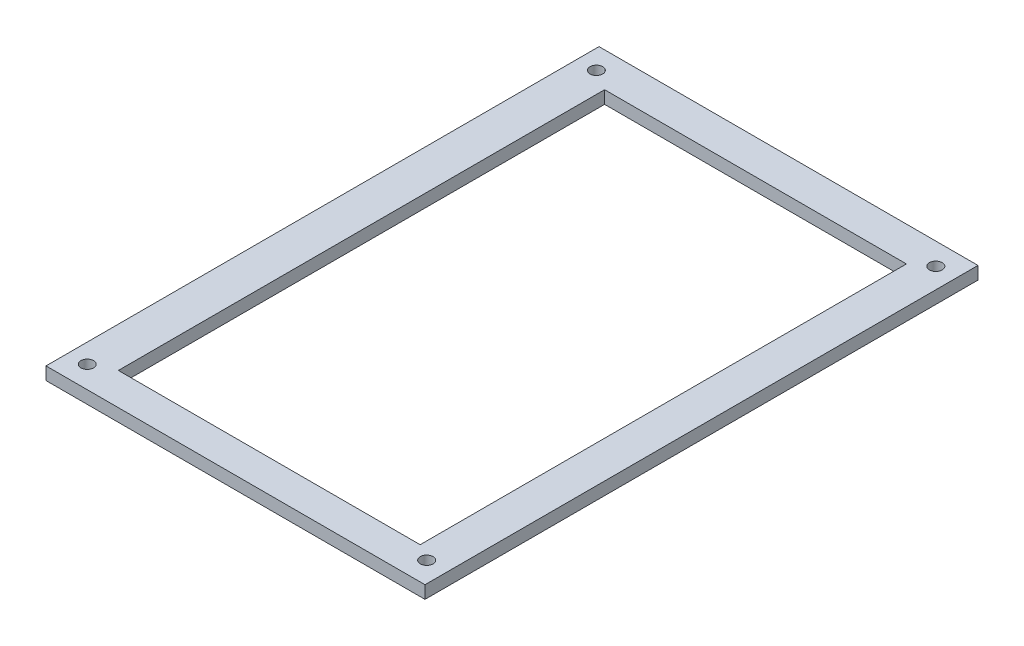
SolidWorks part; units mm, degrees
ref_plane "Front Plane" through (0, 0, 0) normal (0, 0, 1) x (1, 0, 0)
ref_plane "Top Plane" through (0, 0, 0) normal (0, 1, 0) x (1, 0, 0)
ref_plane "Right Plane" through (0, 0, 0) normal (1, 0, 0) x (0, 0, -1)
sketch "Sketch1" plane through (0, 0, 0) normal (0, 1, 0) x (1, 0, 0)
  line L1 (0, 0) -> (97, 0)
  line L2 (0, 0) -> (0, 200)
  line L3 (0, 200) -> (97, 200)
  line L4 (97, 0) -> (97, 200)
  dimension "D1" = 97
  dimension "D2" = 200
extrude "Boss-Extrude1" add sketch "Sketch1" along normal blind 42
sketch "Sketch3" plane through (0, 42, 0) normal (0, 1, 0) x (1, 0, 0)
  line L0 (0, 0) -> (97, 0) construction
  line L1 (97, 0) -> (97, 200) construction
  circle A0 centre (88.5, 61) radius 1.5
  circle A1 centre (8.5, 61) radius 1.5
  circle A2 centre (88.5, 181) radius 1.5
  circle A3 centre (8.5, 181) radius 1.5
  point P12 (0, 0)
  point P13 (0, 0)
  point P14 (0, 0)
  dimension "D1" = 3
  dimension "D2" = 61
  dimension "D3" = 8.5
  dimension "D4" = 80
  dimension "D5" = 61
  dimension "D6" = 120
  dimension "D7" = 120
extrude "Cut-Extrude1" cut sketch "Sketch3" against normal blind 3
sketch "Sketch4" plane through (0, 42, 0) normal (0, 1, 0) x (1, 0, 0)
  line L1 (3.9714, 186.1457) -> (93.2956, 186.1457)
  line L2 (3.9714, 186.1457) -> (3.9714, 55.8052)
  line L3 (3.9714, 55.8052) -> (93.2956, 55.8052)
  line L4 (0, 200) -> (0, 0)
  line L5 (0, 0) -> (97, 0)
  line L6 (97, 0) -> (97, 200)
  line L7 (97, 200) -> (0, 200)
  line L8 (0, 200) -> (0, 0)
  line L9 (0, 0) -> (97, 0)
  line L10 (97, 0) -> (97, 200)
  line L11 (97, 200) -> (0, 200)
  line L12 (93.2956, 186.1457) -> (93.2956, 55.8052)
  dimension "D1" = 0
extrude "Cut-Extrude2" cut sketch "Sketch4" against normal through all
sketch "Sketch5" plane through (0, 42, 0) normal (0, 1, 0) x (1, 0, 0)
  line L1 (13.4247, 178.0102) -> (84.5609, 178.0102)
  line L2 (13.4247, 178.0102) -> (13.4247, 63.4018)
  line L3 (13.4247, 63.4018) -> (84.5609, 63.4018)
  line L4 (84.5609, 178.0102) -> (84.5609, 63.4018)
extrude "Cut-Extrude3" cut sketch "Sketch5" against normal through all
sketch "Sketch6" plane through (0, 0, -186.1457) normal (0, 0, -1) x (-1, 0, 0)
  line L0 (-93.2956, 0) -> (-93.2956, 42) construction
  line L1 (-93.2956, 39) -> (-3.9714, 39)
  line L2 (-93.2956, 39) -> (-93.2956, 0)
  line L3 (-93.2956, 0) -> (-3.9714, 0)
  line L4 (-3.9714, 39) -> (-3.9714, 0)
  line L5 (-93.2956, 42) -> (-3.9714, 42) construction
  dimension "D1" = 3
extrude "Cut-Extrude4" cut sketch "Sketch6" against normal through all
